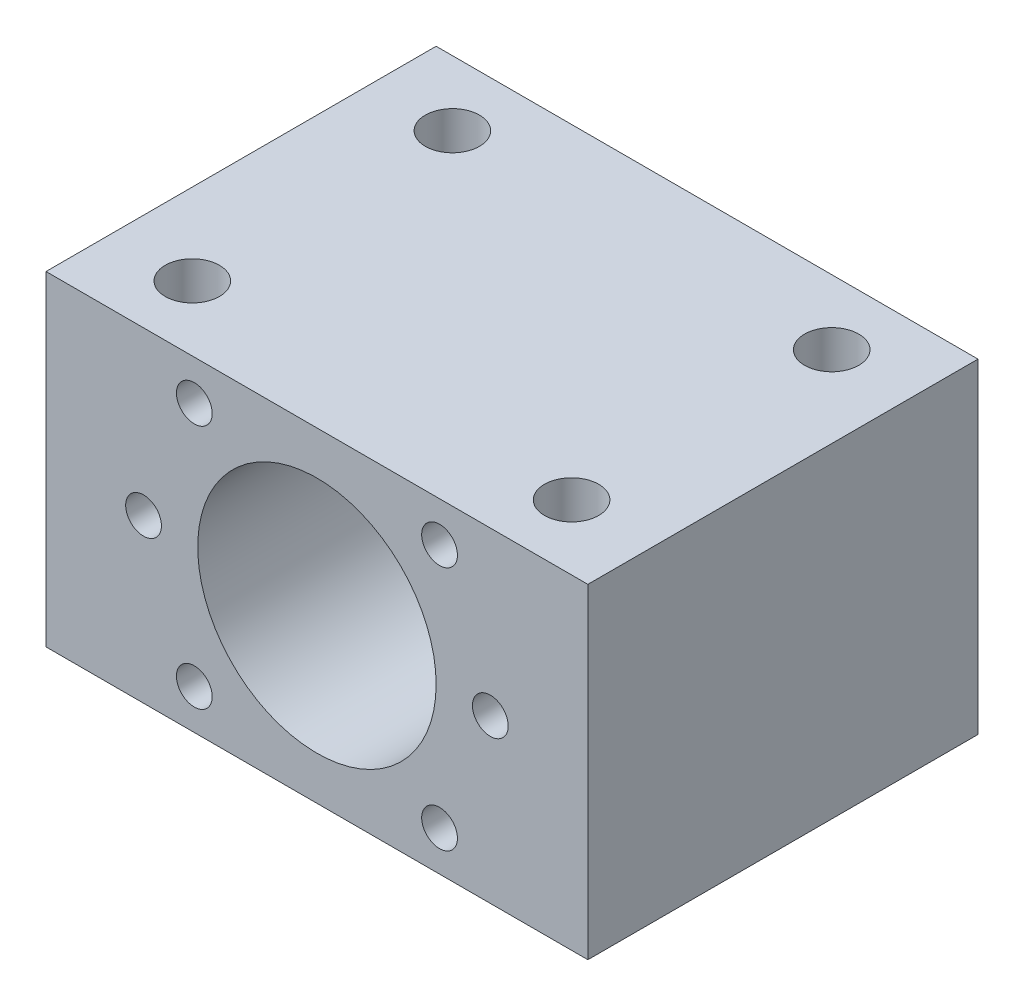
SolidWorks part; units mm, degrees
ref_plane "Front Plane" through (0, 0, 0) normal (0, 0, 1) x (1, 0, 0)
ref_plane "Top Plane" through (0, 0, 0) normal (0, 1, 0) x (1, 0, 0)
ref_plane "Right Plane" through (0, 0, 0) normal (1, 0, 0) x (0, 0, -1)
sketch "Sketch2" plane through (0, 0, 0) normal (0, 0, 1) x (1, 0, 0)
  line L0 (0, 15) -> (0, -15) construction
  line L1 (-25, -15) -> (25, -15)
  line L2 (-25, -15) -> (-25, 15)
  line L3 (-25, 15) -> (25, 15)
  line L4 (25, -15) -> (25, 15)
  line L5 (-25, -15) -> (25, 15) construction
  line L6 (-25, 15) -> (25, -15) construction
  line L7 (0, 0) -> (-16, 0) construction
  line L8 (0, 0) -> (-11.3137, 11.3137) construction
  line L9 (0, 0) -> (-16, 0) construction
  line L10 (0, 0) -> (-11.3137, -11.3137) construction
  circle A0 centre (0, 0) radius 11
  circle A1 centre (-16, 0) radius 2 construction
  circle A2 centre (0, 0) radius 16 construction
  circle A4 centre (-11.3137, 11.3137) radius 2 construction
  circle A5 centre (-11.3137, -11.3137) radius 2 construction
  circle A6 centre (11.3137, -11.3137) radius 2 construction
  circle A7 centre (11.3137, 11.3137) radius 2 construction
  circle A8 centre (16, 0) radius 2 construction
  point P0 (0, 0)
  dimension "D1" = 22
  dimension "D4" = 32
  dimension "D9" = 4
  dimension "D2" = 50
  dimension "D3" = 30
  dimension "D5" = 2
  dimension "D6" = 45
  dimension "D8" = 45
  dimension "D7" = 2
extrude "Boss-Extrude1" add sketch "Sketch2" along normal blind 36
hole_wizard "Tap Drill for M4 Tap1" positions "Sketch3" profile "Sketch4" hole size "M4" standard "ISO"
sketch "Sketch3" plane through (0, 0, 36) normal (0, 0, 1) x (1, 0, 0)
  line L0 (0, 0) -> (-16, 0) construction
  line L1 (0, 0) -> (-16, 0) construction
  line L2 (0, 0) -> (-11.3137, 11.3137) construction
  line L3 (0, 15) -> (0, -15) construction
  line L4 (25, 15) -> (-25, 15) construction
  line L5 (-25, -15) -> (25, -15) construction
  point P2 (-16, 0)
  point P13 (-11.3137, 11.3137)
  point P17 (-11.3137, -11.3137)
  point P26 (11.3137, -11.3137)
  point P27 (16, 0)
  point P28 (11.3137, 11.3137)
  dimension "D1" = 16
  dimension "D3" = 45
  dimension "D2" = 2
sketch "Sketch4" plane through (11.3137, 11.3137, 36) normal (1, 0, 0) x (0, -1, 0)
  line L0 (0, 0) -> (0, 8)
  line L1 (0, 8) -> (1.65, 7.0086)
  line L2 (1.65, 7.0086) -> (1.65, 0)
  line L5 (1.65, 0) -> (0, 0)
  line L10 (0, 8) -> (-1.65, 7.0086) construction
  line L11 (0, -6.35) -> (0, 107.95) construction
  dimension "Hole Dia." = 3.3
  dimension "Hole Depth" = 8
  dimension "Drill Angle" = 118
sketch "Sketch5" plane through (0, 15, 0) normal (0, 1, 0) x (1, 0, 0)
  line L0 (25, -36) -> (-25, -36) construction
  line L1 (17.5, -30) -> (-17.5, -30) construction
  line L2 (17.5, -30) -> (17.5, -6) construction
  line L3 (17.5, -6) -> (-17.5, -6) construction
  line L4 (-17.5, -30) -> (-17.5, -6) construction
  line L7 (25, -36) -> (25, 0) construction
  circle A0 centre (-17.5, -6) radius 2.5
  circle A1 centre (17.5, -6) radius 2.5
  circle A2 centre (17.5, -30) radius 2.5
  circle A3 centre (-17.5, -30) radius 2.5
  dimension "D5" = 5
  dimension "D6" = 5
  dimension "D7" = 5
  dimension "D8" = 5
  dimension "D1" = 6
  dimension "D2" = 24
  dimension "D3" = 35
  dimension "D4" = 7.5
extrude "Cut-Extrude1" cut sketch "Sketch5" against normal blind 12
